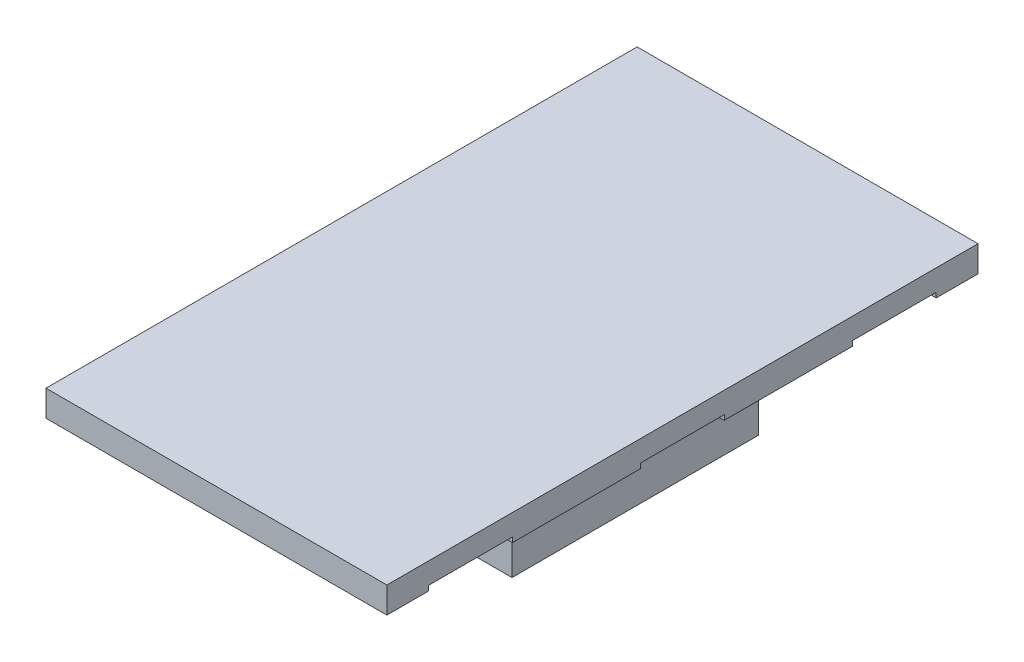
SolidWorks part; units mm, degrees
ref_plane "Спереди" through (0, 0, 0) normal (0, 0, 1) x (1, 0, 0)
ref_plane "Сверху" through (0, 0, 0) normal (0, 1, 0) x (1, 0, 0)
ref_plane "Справа" through (0, 0, 0) normal (1, 0, 0) x (0, 0, -1)
sketch "Sketch1" plane through (0, 0, 0) normal (0, 1, 0) x (1, 0, 0)
  line L1 (3.46, -6) -> (-3.46, -6)
  line L2 (3.46, -6) -> (3.46, 6)
  line L3 (3.46, 6) -> (-3.46, 6)
  line L4 (-3.46, -6) -> (-3.46, 6)
  line L5 (3.46, -6) -> (-3.46, 6) construction
  line L6 (3.46, 6) -> (-3.46, -6) construction
  point P0 (0, 0)
  dimension "D1" = 12
  dimension "D2" = 6.92
extrude "Boss-Extrude1" add sketch "Sketch1" along normal blind 0.53
sketch "Sketch2" plane through (0, 0, 0) normal (0, -1, 0) x (1, 0, 0)
  line L1 (2.5, 2.5) -> (-2.5, 2.5)
  line L2 (2.5, 2.5) -> (2.5, -2.5)
  line L3 (2.5, -2.5) -> (-2.5, -2.5)
  line L4 (-2.5, 2.5) -> (-2.5, -2.5)
  line L5 (2.5, 2.5) -> (-2.5, -2.5) construction
  line L6 (2.5, -2.5) -> (-2.5, 2.5) construction
  point P0 (0, 0)
  dimension "D1" = 5
  dimension "D2" = 5
extrude "Boss-Extrude2" add sketch "Sketch2" along normal blind 1.57
sketch "Sketch3" plane through (0, -1.57, 0) normal (0, -1, 0) x (1, 0, 0)
  circle A0 centre (0, 0) radius 2
extrude "Cut-Extrude1" cut sketch "Sketch3" against normal blind 0.2
chamfer "Chamfer1" distance 0.1 angle 45 1 edges at (0, -1.57, -2)
sketch "Sketch4" plane through (0, 0, 0) normal (0, -1, 0) x (1, 0, 0)
  line L0 (0, 6.476) -> (0, -6.9083) construction
  line L5 (3.46, 0.85) -> (3.46, -0.85)
  line L6 (3.46, 5.1515) -> (2.351, 5.1515)
  line L7 (2.351, 3.4515) -> (3.46, 3.4515)
  line L8 (3.46, -6) -> (-3.46, -6) construction
  line L9 (3.46, 3.4515) -> (3.46, 5.1515)
  line L11 (3.46, -5.1515) -> (2.351, -5.1515)
  line L13 (-2.351, -3.4515) -> (-3.46, -3.4515)
  line L14 (-3.46, -3.4515) -> (-3.46, -5.1515)
  line L15 (-3.46, -5.1515) -> (-2.351, -5.1515)
  line L16 (-9.0262, 0) -> (8.7663, 0) construction
  line L17 (-3.46, 3.4515) -> (-3.46, 5.1515)
  line L18 (-2.351, 3.4515) -> (-3.46, 3.4515)
  line L19 (-3.46, 5.1515) -> (-2.351, 5.1515)
  line L20 (-3.46, -6) -> (-3.46, 6) construction
  line L21 (-3.46, 0.85) -> (-3.46, -0.85)
  line L22 (3.46, -3.4515) -> (3.46, -5.1515)
  line L23 (2.351, -3.4515) -> (3.46, -3.4515)
  arc A2 (-2.351, -3.4515) -> (-2.351, -5.1515) centre (-2.351, -4.3015) cw
  arc A4 (-2.351, 3.4515) -> (-2.351, 5.1515) centre (-2.351, 4.3015) ccw
  arc A5 (-3.46, 0.85) -> (-3.46, -0.85) centre (-3.46, 0) cw
  arc A6 (3.46, 0.85) -> (3.46, -0.85) centre (3.46, 0) ccw
  arc A7 (2.351, 3.4515) -> (2.351, 5.1515) centre (2.351, 4.3015) cw
  arc A8 (2.351, -3.4515) -> (2.351, -5.1515) centre (2.351, -4.3015) ccw
  point P14 (-2.5468, -6)
  point P38 (2.5468, -6)
  dimension "D5" = 0.85
  dimension "D6" = 0.85
  dimension "D4" = 1.7
sketch "Sketch6" plane through (0, 0, 0) normal (0, -1, 0) x (1, 0, 0)
  line L1 (-1, -4.85) -> (1, -4.85)
  line L2 (-1, -4.85) -> (-1, -3.65)
  line L3 (-1, -3.65) -> (1, -3.65)
  line L4 (1, -4.85) -> (1, -3.65)
extrude "Boss-Extrude3" add sketch "Sketch6" along normal blind 0.45
extrude "Cut-Extrude2" cut sketch "Sketch4" against normal blind 0.1
sketch "Sketch7" plane through (0, 0.53, 0) normal (0, 1, 0) x (1, 0, 0)
  line L0 (3.46, 0) -> (-3.46, 0) construction
  line L1 (3.46, -6) -> (3.46, 6) construction
  line L2 (-3.46, 6) -> (-3.46, -6) construction
